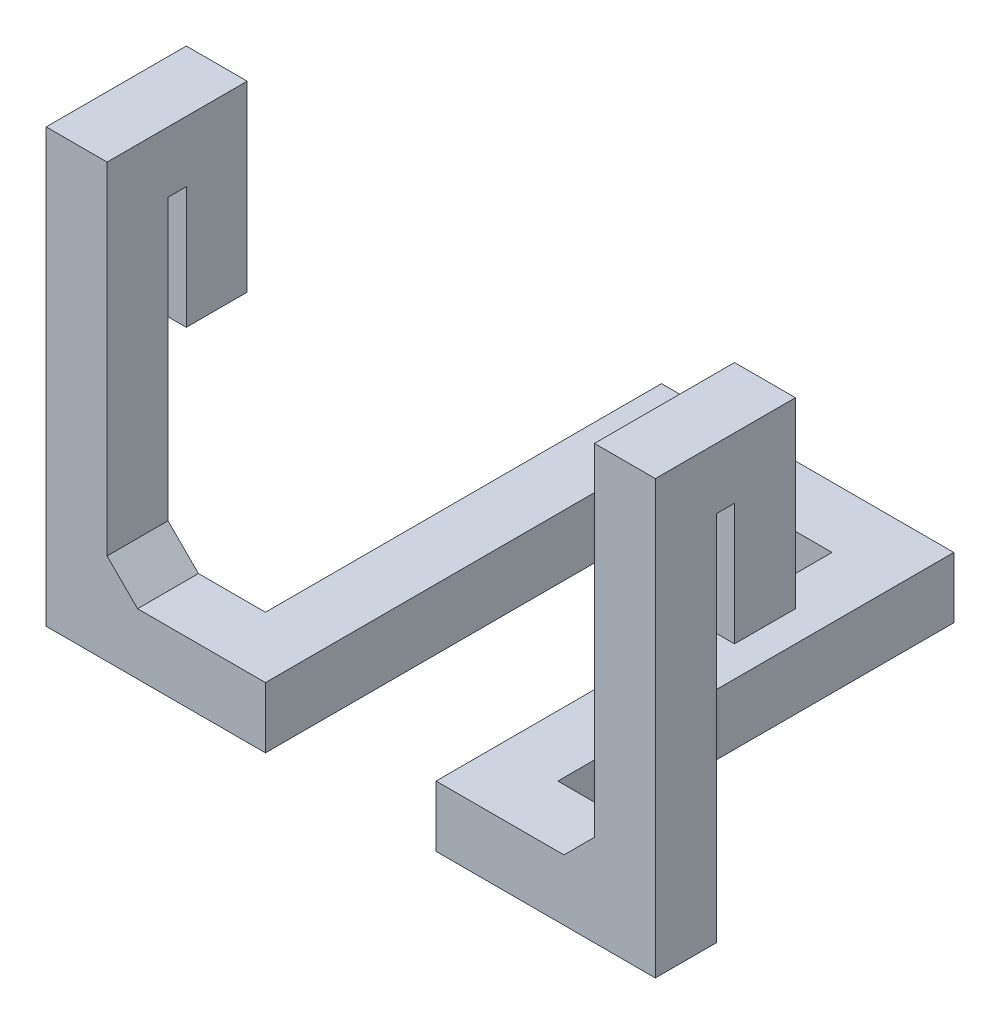
SolidWorks part; units mm, degrees
ref_plane "Front Plane" through (0, 0, 0) normal (0, 0, 1) x (1, 0, 0)
ref_plane "Top Plane" through (0, 0, 0) normal (0, 1, 0) x (1, 0, 0)
ref_plane "Right Plane" through (0, 0, 0) normal (1, 0, 0) x (0, 0, -1)
sketch "Sketch1" plane through (0, 0, 0) normal (1, 0, 0) x (0, 0, -1)
  line L1 (0, 0) -> (0, 71)
  line L2 (0, 71) -> (23, 71)
  line L3 (23, 71) -> (23, 41)
  line L5 (10, 0) -> (10, 61)
  line L6 (10, 61) -> (13, 61)
  line L7 (13, 61) -> (13, 41)
  line L8 (13, 41) -> (23, 41)
  line L10 (0, 0) -> (10, 0)
  line L11 (0, -24.389) -> (0, 0) construction
  line L12 (10, -24.389) -> (10, 0) construction
  dimension "D2" = 20
  dimension "D3" = 3
  dimension "D4" = 71
  dimension "D1" = 10
extrude "Boss-Extrude1" add sketch "Sketch1" along normal blind 10
sketch "Sketch2" plane through (0, 0, 0) normal (0, 1, 0) x (1, 0, 0)
  line L0 (50, 65) -> (50, 0) construction
  line L1 (10, 0) -> (36, 0)
  line L2 (36, 0) -> (36, 65)
  line L3 (36, 65) -> (50, 65)
  line L4 (10, 10) -> (26, 10)
  line L5 (26, 10) -> (26, 75)
  line L6 (26, 75) -> (50, 75)
  line L7 (10, 10) -> (10, 0)
  line L8 (90, 10) -> (90, 0)
  line L9 (74, 75) -> (50, 75)
  line L10 (74, 10) -> (74, 75)
  line L11 (90, 10) -> (74, 10)
  line L12 (64, 65) -> (50, 65)
  line L13 (64, 0) -> (64, 65)
  line L14 (90, 0) -> (64, 0)
  dimension "D1" = 10
  dimension "D2" = 80
  dimension "D3" = 28
  dimension "D4" = 65
extrude "Boss-Extrude2" add sketch "Sketch2" along normal blind 10
sketch "Sketch3" plane through (90, 0, 0) normal (1, 0, 0) x (0, 0, -1)
  line L8 (0, 71) -> (0, 0)
  line L9 (23, 71) -> (0, 71)
  line L10 (23, 41) -> (23, 71)
  line L11 (13, 41) -> (23, 41)
  line L12 (13, 61) -> (13, 41)
  line L13 (10, 61) -> (13, 61)
  line L14 (10, 0) -> (10, 61)
  line L15 (0, 0) -> (10, 0)
  line L16 (0, 71) -> (0, 0)
  line L17 (23, 71) -> (0, 71)
  line L18 (23, 41) -> (23, 71)
  line L19 (13, 41) -> (23, 41)
  line L20 (13, 61) -> (13, 41)
  line L21 (10, 61) -> (13, 61)
  line L22 (10, 0) -> (10, 61)
  line L23 (0, 0) -> (10, 0)
  dimension "D1" = 0
extrude "Boss-Extrude3" add sketch "Sketch3" along normal blind 10
sketch "Sketch4" plane through (10, 0, 0) normal (1, 0, 0) x (0, 0, -1)
  line L1 (0, 71) -> (10, 71)
  line L2 (0, 71) -> (0, 61)
  line L3 (0, 61) -> (10, 61)
  line L4 (10, 71) -> (10, 61)
extrude "Boss-Extrude4" [suppressed] add sketch "Sketch4" along normal up to next
fillet "Fillet1" radius 5 2 edges at (10, 10, -5) (90, 10, -5) profile chamfer
equation "\"t\"= 10mm"
equation "\"D1@Boss-Extrude1\"=\"t\""
equation "\"D1@Sketch2\"=\"t\""
equation "\"D1@Boss-Extrude2\"=\"t\""
equation "\"D1@Boss-Extrude3\"=\"t\""
equation "\"D4@Sketch2\"=\"t\"+55"
